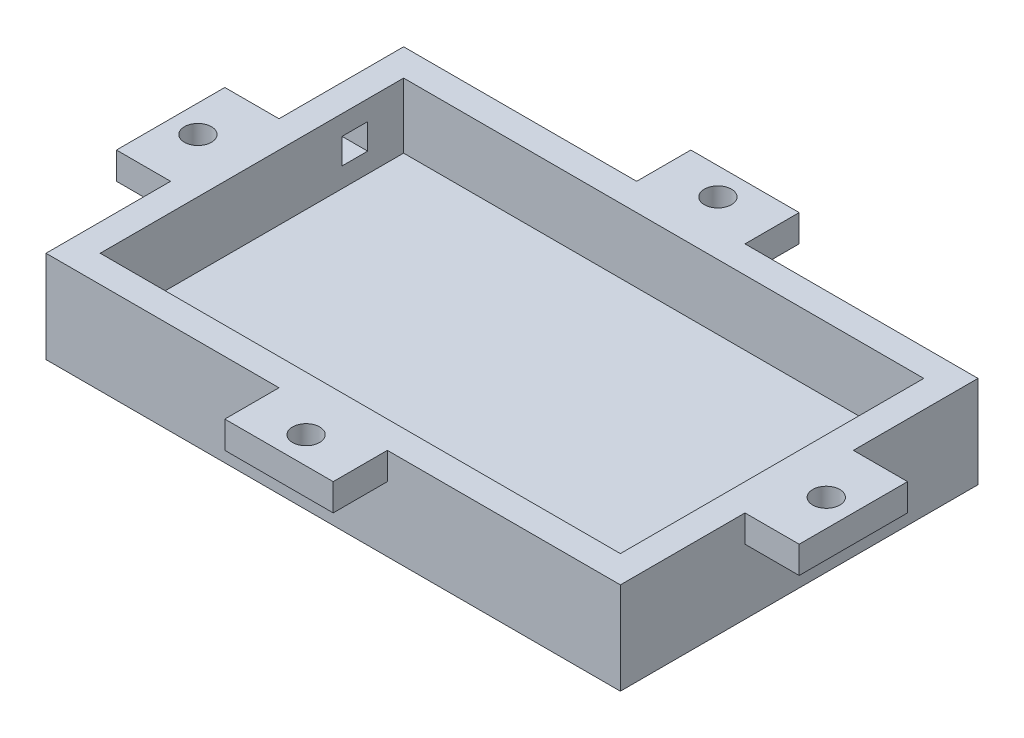
SolidWorks part; units mm, degrees
ref_plane "Front Plane" through (0, 0, 0) normal (0, 0, 1) x (1, 0, 0)
ref_plane "Top Plane" through (0, 0, 0) normal (0, 1, 0) x (1, 0, 0)
ref_plane "Right Plane" through (0, 0, 0) normal (1, 0, 0) x (0, 0, -1)
sketch "Sketch1" plane through (0, 0, 0) normal (0, 1, 0) x (1, 0, 0)
  line L1 (-30.48, 17.78) -> (30.48, 17.78)
  line L2 (-30.48, 17.78) -> (-30.48, -17.78)
  line L3 (-30.48, -17.78) -> (30.48, -17.78)
  line L4 (30.48, 17.78) -> (30.48, -17.78)
  line L5 (-30.48, 17.78) -> (30.48, -17.78) construction
  line L6 (-30.48, -17.78) -> (30.48, 17.78) construction
  line L7 (-33.655, 20.955) -> (33.655, 20.955)
  line L8 (-33.655, 20.955) -> (-33.655, -20.955)
  line L9 (-33.655, -20.955) -> (33.655, -20.955)
  line L10 (33.655, 20.955) -> (33.655, -20.955)
  line L11 (-33.655, 20.955) -> (33.655, -20.955) construction
  line L12 (-33.655, -20.955) -> (33.655, 20.955) construction
  point P0 (0, 0)
  point P6 (0, 0)
  dimension "D1" = 60.96
  dimension "D2" = 35.56
  dimension "D3" = 67.31
  dimension "D4" = 41.91
extrude "Boss-Extrude5" add sketch "Sketch1" along normal blind 3.175 contours L8 L7 L10 L9
sketch "Sketch2" plane through (0, 3.175, 0) normal (0, 1, 0) x (1, 0, 0)
  line L1 (-30.48, 17.78) -> (30.48, 17.78)
  line L2 (-30.48, 17.78) -> (-30.48, -17.78)
  line L3 (-30.48, -17.78) -> (30.48, -17.78)
  line L4 (30.48, 17.78) -> (30.48, -17.78)
  line L5 (-30.48, 17.78) -> (30.48, -17.78) construction
  line L6 (-30.48, -17.78) -> (30.48, 17.78) construction
  line L7 (-33.655, 20.955) -> (33.655, 20.955)
  line L8 (-33.655, 20.955) -> (-33.655, -20.955)
  line L9 (-33.655, -20.955) -> (33.655, -20.955)
  line L10 (33.655, 20.955) -> (33.655, -20.955)
  line L11 (-33.655, 20.955) -> (33.655, -20.955) construction
  line L12 (-33.655, -20.955) -> (33.655, 20.955) construction
  point P0 (0, 0)
  point P6 (0, 0)
  dimension "D1" = 60.96
  dimension "D2" = 35.56
extrude "Boss-Extrude6" add sketch "Sketch2" along normal blind 7.62
sketch "Sketch4" plane through (0, 10.795, 0) normal (0, 1, 0) x (1, 0, 0)
  line L0 (33.655, 0) -> (40.005, 0)
  line L1 (33.655, -20.955) -> (33.655, 20.955) construction
  line L2 (0, -20.955) -> (0, -27.305)
  line L3 (-33.655, -20.955) -> (33.655, -20.955) construction
  line L4 (0, 20.955) -> (0, 27.305)
  line L5 (33.655, 20.955) -> (-33.655, 20.955) construction
  line L6 (-33.655, 0) -> (-40.005, 0)
  line L7 (-33.655, 20.955) -> (-33.655, -20.955) construction
  line L9 (-6.35, -20.955) -> (6.35, -20.955)
  line L10 (-6.35, -20.955) -> (-6.35, -27.305)
  line L11 (-6.35, -27.305) -> (6.35, -27.305)
  line L12 (6.35, -20.955) -> (6.35, -27.305)
  line L13 (-6.35, -20.955) -> (6.35, -27.305) construction
  line L14 (-6.35, -27.305) -> (6.35, -20.955) construction
  line L15 (-6.35, 27.305) -> (6.35, 27.305)
  line L16 (-6.35, 27.305) -> (-6.35, 20.955)
  line L17 (-6.35, 20.955) -> (6.35, 20.955)
  line L18 (6.35, 27.305) -> (6.35, 20.955)
  line L19 (-6.35, 27.305) -> (6.35, 20.955) construction
  line L20 (-6.35, 20.955) -> (6.35, 27.305) construction
  line L21 (33.655, 6.35) -> (40.005, 6.35)
  line L22 (33.655, 6.35) -> (33.655, -6.35)
  line L23 (33.655, -6.35) -> (40.005, -6.35)
  line L24 (40.005, 6.35) -> (40.005, -6.35)
  line L25 (33.655, 6.35) -> (40.005, -6.35) construction
  line L26 (33.655, -6.35) -> (40.005, 6.35) construction
  line L27 (-40.005, 6.35) -> (-33.655, 6.35)
  line L28 (-40.005, 6.35) -> (-40.005, -6.35)
  line L29 (-40.005, -6.35) -> (-33.655, -6.35)
  line L30 (-33.655, 6.35) -> (-33.655, -6.35)
  line L31 (-40.005, 6.35) -> (-33.655, -6.35) construction
  line L32 (-40.005, -6.35) -> (-33.655, 6.35) construction
  point P17 (0, -24.13)
  point P22 (0, 24.13)
  point P27 (36.83, 0)
  point P32 (-36.83, 0)
  dimension "D1" = 6.35
  dimension "D2" = 6.35
  dimension "D3" = 6.35
  dimension "D4" = 6.35
  dimension "D5" = 12.7
  dimension "D6" = 12.7
  dimension "D7" = 12.7
  dimension "D8" = 12.7
extrude "Boss-Extrude8" add sketch "Sketch4" against normal blind 3.175 contours L29 L30 L27 L28 | L18 L17 L16 L15 | L23 L24 L21 L22 | L12 L11 L10 L9
sketch "Sketch6" plane through (0, 10.795, 0) normal (0, 1, 0) x (1, 0, 0)
  line L0 (-40.005, 0) -> (-33.6078, 0)
  line L1 (-40.005, 6.35) -> (-40.005, -6.35) construction
  line L2 (-33.6078, 0) -> (-33.655, 6.35)
  line L3 (-33.655, 6.35) -> (-33.655, -6.35)
  line L4 (-40.005, -6.35) -> (-33.655, -6.35) construction
  line L5 (-6.35, 20.955) -> (6.35, 20.955)
  line L6 (0, 20.955) -> (0, 27.305)
  line L7 (-6.35, 27.305) -> (6.35, 27.305) construction
  line L8 (33.655, 6.35) -> (33.655, -6.35)
  line L9 (40.005, 6.35) -> (40.005, -6.35) construction
  line L10 (40.005, 0) -> (33.655, 0)
  line L11 (-6.35, -20.955) -> (6.35, -20.955)
  line L12 (0, -20.955) -> (0, -27.305)
  line L13 (-6.35, -27.305) -> (6.35, -27.305) construction
  circle A0 centre (-36.8064, 0) radius 1.5875
  circle A1 centre (36.83, 0) radius 1.5875
  circle A2 centre (0, -24.13) radius 1.5875
  circle A3 centre (0, 24.13) radius 1.5875
extrude "Cut-Extrude1" cut sketch "Sketch6" against normal through all contours L6 A3 | A0 | A1 | A2
sketch "Sketch7" plane through (-30.48, 0, 0) normal (1, 0, 0) x (0, 0, -1)
  line L0 (17.78, 6.985) -> (-18.5716, 6.985)
  line L1 (17.78, 10.795) -> (17.78, 3.175) construction
  line L2 (6.3512, 10.795) -> (6.3512, 3.175)
  line L3 (17.78, 10.795) -> (-17.78, 10.795) construction
  line L4 (17.78, 3.175) -> (-17.78, 3.175) construction
  line L6 (6.3512, 10.795) -> (17.78, 10.795)
  line L7 (6.3512, 10.795) -> (6.3512, 3.175)
  line L8 (6.3512, 3.175) -> (17.78, 3.175)
  line L9 (17.78, 10.795) -> (17.78, 3.175)
  line L10 (10.5656, 8.485) -> (13.5656, 8.485)
  line L11 (10.5656, 8.485) -> (10.5656, 5.485)
  line L12 (10.5656, 5.485) -> (13.5656, 5.485)
  line L13 (13.5656, 8.485) -> (13.5656, 5.485)
  line L14 (10.5656, 8.485) -> (13.5656, 5.485) construction
  line L15 (10.5656, 5.485) -> (13.5656, 8.485) construction
  point P12 (12.0656, 6.985)
  dimension "D1" = 3
  dimension "D2" = 3
extrude "Cut-Extrude2" cut sketch "Sketch7" against normal through all contours L10 L13 L12 L11
